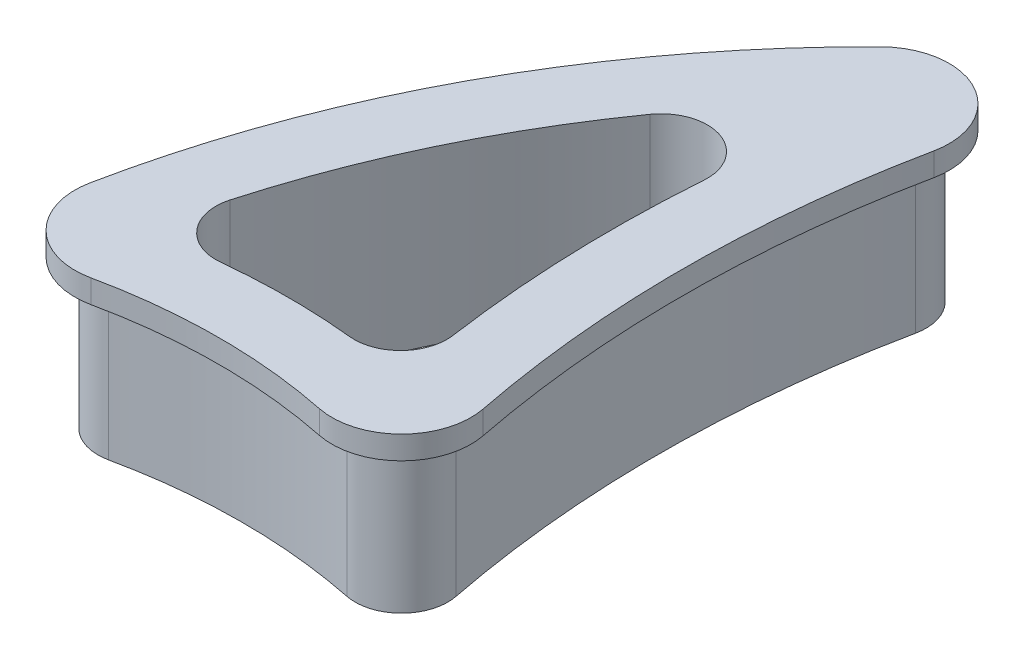
SolidWorks part; units mm, degrees
ref_plane "前视基准面" through (0, 0, 0) normal (0, 0, 1) x (1, 0, 0)
ref_plane "上视基准面" through (0, 0, 0) normal (0, 1, 0) x (1, 0, 0)
ref_plane "右视基准面" through (0, 0, 0) normal (1, 0, 0) x (0, 0, -1)
other "Configuration Table"
sketch "草图1" plane through (0, 0, 0) normal (0, 1, 0) x (1, 0, 0)
  arc A0 (2.8296, -15.5299) -> (2.9104, 4.2292) centre (51.8838, -5.8508) cw
  arc A1 (-0.4528, 6.0566) -> (-12.1404, -15.571) centre (29.0354, -23.8508) ccw
  arc A2 (-9.762, -17.9212) -> (0.4668, -17.8765) centre (-4.5408, -42.3699) cw
  arc A3 (-12.1404, -15.571) -> (-9.762, -17.9212) centre (-10.1797, -15.9653) ccw
  arc A4 (0.4668, -17.8765) -> (2.8296, -15.5299) centre (0.8674, -15.9171) ccw
  arc A5 (-0.4528, 6.0566) -> (2.9104, 4.2292) centre (0.9514, 4.6324) cw
  arc A6 (-3.602, -0.725) -> (-9.4595, -12.9814) centre (29.0354, -23.8508) ccw
  arc A8 (-7.3283, -15.5142) -> (-1.7735, -15.5121) centre (-4.5408, -42.3699) cw
  arc A10 (0.4112, -13.2385) -> (0.0245, -2.0283) centre (51.8838, -5.8508) cw
  arc A12 (0.9514, 4.6324) -> (-10.1797, -15.9653) centre (29.0354, -23.8508) ccw construction
  arc A13 (-10.1797, -15.9653) -> (0.8674, -15.9171) centre (-4.5408, -42.3699) cw construction
  arc A14 (-9.4595, -12.9814) -> (-7.3283, -15.5142) centre (-7.5348, -13.5249) ccw
  arc A15 (-10.1797, -15.9653) -> (-10.1797, -15.9653) centre (-10.1797, -15.9653) ccw construction
  arc A16 (0.8674, -15.9171) -> (0.9514, 4.6324) centre (51.8838, -5.8508) cw construction
  arc A17 (-1.7735, -15.5121) -> (0.4112, -13.2385) centre (-1.5685, -13.5226) ccw
  arc A18 (0.8674, -15.9171) -> (0.8674, -15.9171) centre (0.8674, -15.9171) ccw construction
  arc A19 (0.0245, -2.0283) -> (-3.602, -0.725) centre (-1.9701, -1.8813) ccw
  arc A20 (0.9514, 4.6324) -> (0.9514, 4.6324) centre (0.9514, 4.6324) cw construction
  dimension "D2" = 2
  dimension "D1" = 2
extrude "凸台-拉伸1" add sketch "草图1" along normal blind 6.4
sketch "草图2" plane through (0, 6.4, 0) normal (0, 1, 0) x (1, 0, 0)
  arc A12 (3.8898, 4.0276) -> (3.8106, -15.3363) centre (51.8838, -5.8508) ccw
  arc A13 (3.8898, 4.0276) -> (-1.1549, 6.7686) centre (0.9514, 4.6324) ccw
  arc A14 (-1.1549, 6.7686) -> (-13.1208, -15.3739) centre (29.0354, -23.8508) ccw
  arc A15 (-13.1208, -15.3739) -> (-9.5531, -18.8991) centre (-10.1797, -15.9653) ccw
  arc A16 (0.2665, -18.8563) -> (-9.5531, -18.8991) centre (-4.5408, -42.3699) ccw
  arc A17 (0.2665, -18.8563) -> (3.8106, -15.3363) centre (0.8674, -15.9171) ccw
  arc A18 (3.8898, 4.0276) -> (3.8106, -15.3363) centre (51.8838, -5.8508) ccw
  arc A19 (3.8898, 4.0276) -> (-1.1549, 6.7686) centre (0.9514, 4.6324) ccw
  arc A20 (-1.1549, 6.7686) -> (-13.1208, -15.3739) centre (29.0354, -23.8508) ccw
  arc A21 (-13.1208, -15.3739) -> (-9.5531, -18.8991) centre (-10.1797, -15.9653) ccw
  arc A22 (0.2665, -18.8563) -> (-9.5531, -18.8991) centre (-4.5408, -42.3699) ccw
  arc A23 (0.2665, -18.8563) -> (3.8106, -15.3363) centre (0.8674, -15.9171) ccw
  arc A30 (0.0245, -2.0283) -> (0.4112, -13.2385) centre (51.8838, -5.8508) ccw
  arc A31 (-1.7735, -15.5121) -> (0.4112, -13.2385) centre (-1.5685, -13.5226) ccw
  arc A32 (-1.7735, -15.5121) -> (-7.3283, -15.5142) centre (-4.5408, -42.3699) ccw
  arc A33 (-9.4595, -12.9814) -> (-7.3283, -15.5142) centre (-7.5348, -13.5249) ccw
  arc A34 (-3.602, -0.725) -> (-9.4595, -12.9814) centre (29.0354, -23.8508) ccw
  arc A35 (0.0245, -2.0283) -> (-3.602, -0.725) centre (-1.9701, -1.8813) ccw
  arc A36 (0.0245, -2.0283) -> (0.4112, -13.2385) centre (51.8838, -5.8508) ccw
  arc A37 (-1.7735, -15.5121) -> (0.4112, -13.2385) centre (-1.5685, -13.5226) ccw
  arc A38 (-1.7735, -15.5121) -> (-7.3283, -15.5142) centre (-4.5408, -42.3699) ccw
  arc A39 (-9.4595, -12.9814) -> (-7.3283, -15.5142) centre (-7.5348, -13.5249) ccw
  arc A40 (-3.602, -0.725) -> (-9.4595, -12.9814) centre (29.0354, -23.8508) ccw
  arc A41 (0.0245, -2.0283) -> (-3.602, -0.725) centre (-1.9701, -1.8813) ccw
  dimension "D1" = 1
  dimension "D2" = 0
extrude "凸台-拉伸2" add sketch "草图2" along normal blind 1
